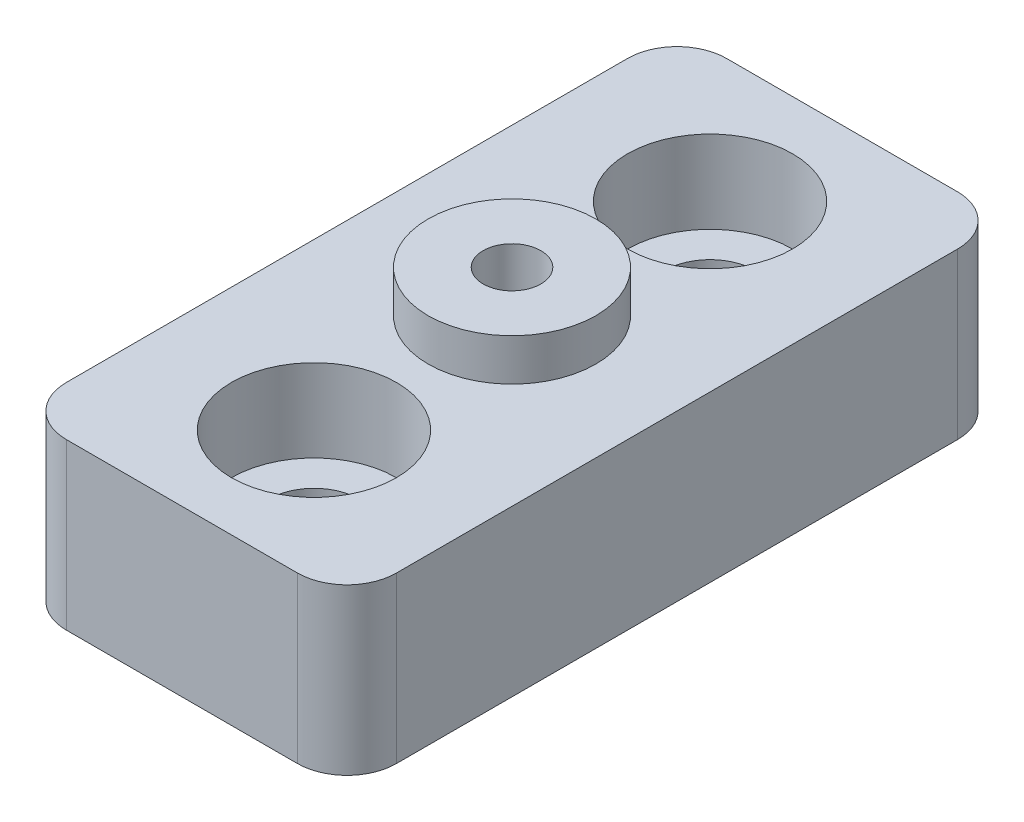
SolidWorks part; units mm, degrees
ref_plane "Front Plane" through (0, 0, 0) normal (0, 0, 1) x (1, 0, 0)
ref_plane "Top Plane" through (0, 0, 0) normal (0, 1, 0) x (1, 0, 0)
ref_plane "Right Plane" through (0, 0, 0) normal (1, 0, 0) x (0, 0, -1)
sketch "Sketch1" plane through (0, 0, 0) normal (0, 1, 0) x (1, 0, 0)
  line L1 (-10, 20) -> (10, 20)
  line L2 (-10, 20) -> (-10, -20)
  line L3 (-10, -20) -> (10, -20)
  line L4 (10, 20) -> (10, -20)
  line L5 (-10, 20) -> (10, -20) construction
  line L6 (-10, -20) -> (10, 20) construction
  point P0 (0, 0)
  dimension "D1" = 40
  dimension "D2" = 20
extrude "Boss-Extrude1" add sketch "Sketch1" along normal blind 10
sketch "Sketch2" plane through (0, 10, 0) normal (0, 1, 0) x (1, 0, 0)
  line L0 (0, 12) -> (0, -12)
  point P4 (0, 0)
  dimension "D1" = 12
sketch "Sketch3" plane through (0, 10, 0) normal (0, 1, 0) x (1, 0, 0)
  line L1 (3.1754, 0) -> (1.5877, 2.75)
  line L2 (1.5877, 2.75) -> (-1.5877, 2.75)
  line L3 (-1.5877, 2.75) -> (-3.1754, 0)
  line L4 (-3.1754, 0) -> (-1.5877, -2.75)
  line L5 (-1.5877, -2.75) -> (1.5877, -2.75)
  line L6 (1.5877, -2.75) -> (3.1754, 0)
  circle A0 centre (0, 0) radius 2.75 construction
  point P1 (1.5502, -2.7713)
  dimension "D1" = 5.5
extrude "Cut-Extrude1" cut sketch "Sketch3" against normal through all draft 1 from offset 2 offset against normal yes draft outward yes
sketch "Sketch4" plane through (0, 10, 0) normal (0, 1, 0) x (1, 0, 0)
  circle A0 centre (0, 0) radius 5.08
  dimension "D1" = 10.16
extrude "Boss-Extrude2" add sketch "Sketch4" along normal blind 2.54
sketch "Sketch5" plane through (0, 8, 0) normal (0, -1, 0) x (1, 0, 0)
  circle A0 centre (0, 0) radius 1.75
  dimension "D1" = 3.5
extrude "Cut-Extrude2" cut sketch "Sketch5" against normal through all
hole_wizard "CBORE for M5 SHCS1" positions "Sketch7" profile "Sketch8" counterbore size "M5" standard "ANSI Metric"
sketch "Sketch7" plane through (0, 10, 0) normal (0, 1, 0) x (1, 0, 0)
  point P0 (0, -12)
  point P3 (0, 12)
sketch "Sketch8" plane through (0, 10, 12) normal (1, 0, 0) x (0, 0, 1)
  line L0 (0, 0) -> (0, 13.6524)
  line L1 (0, 13.6524) -> (2.75, 12)
  line L2 (2.75, 12) -> (2.75, 5)
  line L3 (2.75, 5) -> (5, 5)
  line L4 (5, 5) -> (5, 0)
  line L5 (5, 0) -> (0, 0)
  line L10 (0, 13.6524) -> (-2.75, 12) construction
  line L11 (0, -6.35) -> (0, 107.95) construction
  dimension "Hole Dia." = 5.5
  dimension "Hole Depth" = 12
  dimension "C'Bore Dia." = 10
  dimension "C'Bore Depth" = 5
  dimension "Drill Angle" = 118
fillet "Fillet1" radius 3 4 edges at (-10, 5, 20) (10, 5, 20) (-10, 5, -20) (10, 5, -20)
